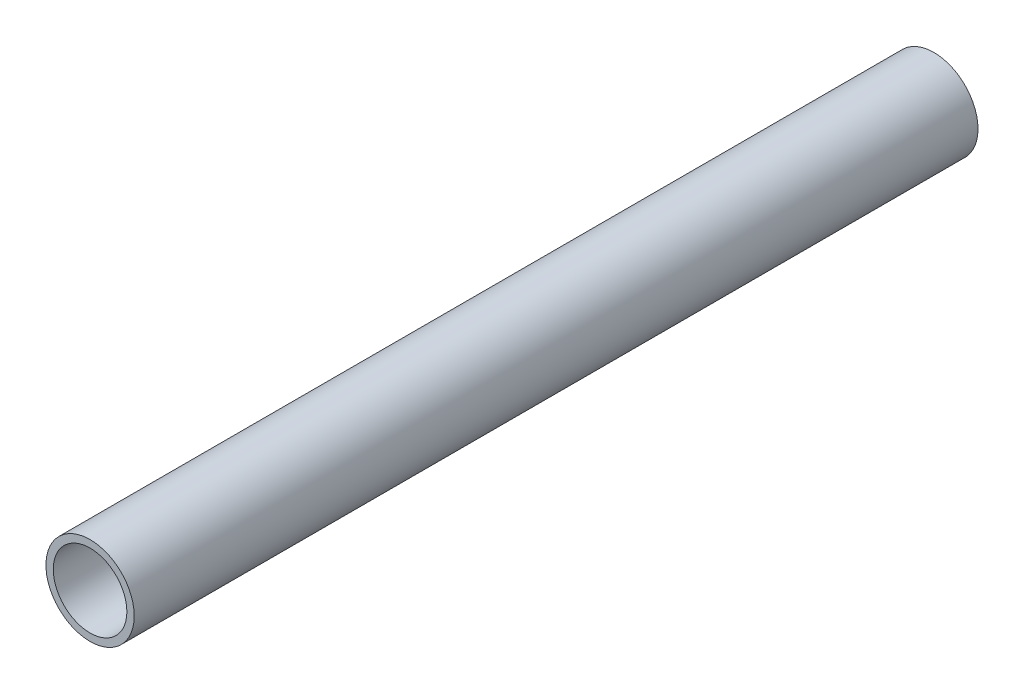
SolidWorks part; units mm, degrees
material "Thornel Mat VMA"
ref_plane "Front Plane" through (0, 0, 0) normal (0, 0, 1) x (1, 0, 0)
ref_plane "Top Plane" through (0, 0, 0) normal (0, 1, 0) x (1, 0, 0)
ref_plane "Right Plane" through (0, 0, 0) normal (1, 0, 0) x (0, 0, -1)
sketch "Sketch1" plane through (0, 0, 0) normal (0, 0, 1) x (1, 0, 0)
  circle A0 centre (0, 0) radius 9
  circle A1 centre (0, 0) radius 7.5
  dimension "D1" = 18
  dimension "D2" = 15
extrude "Boss-Extrude1" add sketch "Sketch1" along normal blind 172
